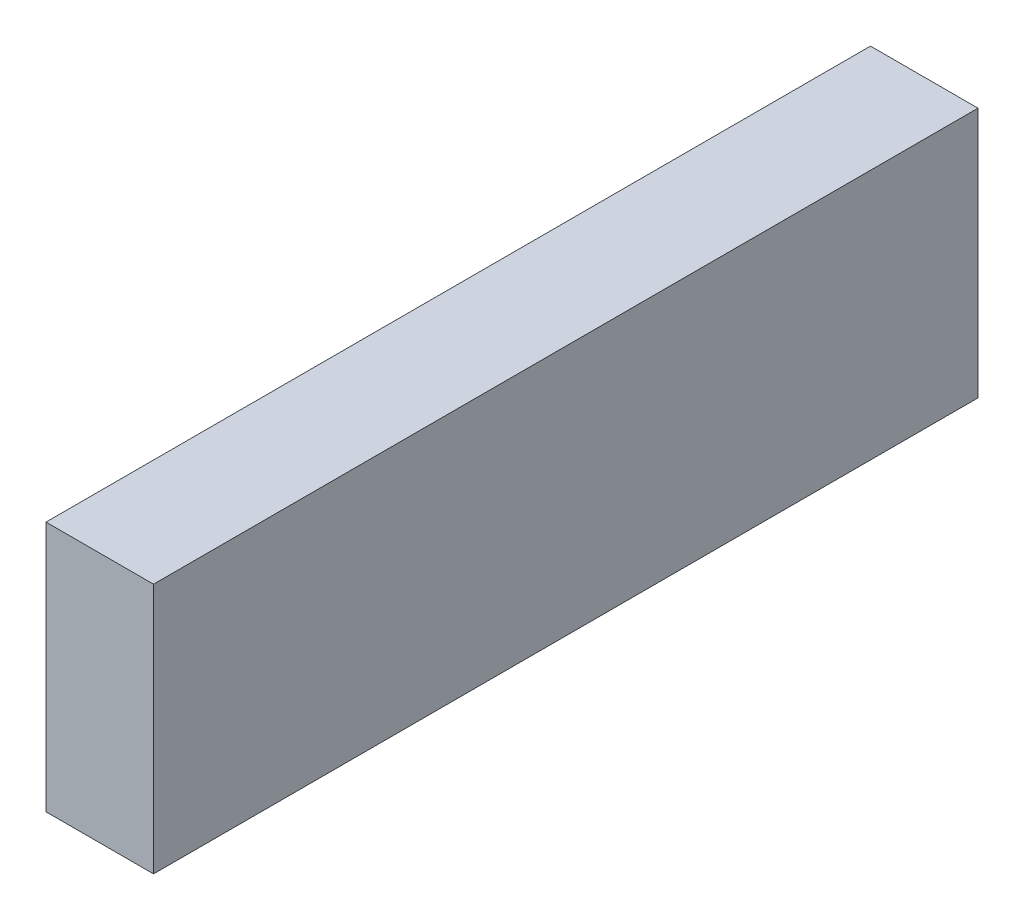
SolidWorks part; units mm, degrees
ref_plane "Front Plane" through (0, 0, 0) normal (0, 0, 1) x (1, 0, 0)
ref_plane "Top Plane" through (0, 0, 0) normal (0, 1, 0) x (1, 0, 0)
ref_plane "Right Plane" through (0, 0, 0) normal (1, 0, 0) x (0, 0, -1)
sketch "Sketch1" plane through (0, 0, 0) normal (0, 0, 1) x (1, 0, 0)
  line L0 (914.4, 1060.45) -> (0, 1060.45) construction
  line L1 (914.4, 1149.35) -> (876.3, 1149.35)
  line L2 (914.4, 1149.35) -> (914.4, 1060.45)
  line L3 (914.4, 1060.45) -> (876.3, 1060.45)
  line L4 (876.3, 1149.35) -> (876.3, 1060.45)
  dimension "D1" = 38.1
extrude "Boss-Extrude1" add sketch "Sketch1" along normal blind 292.1
